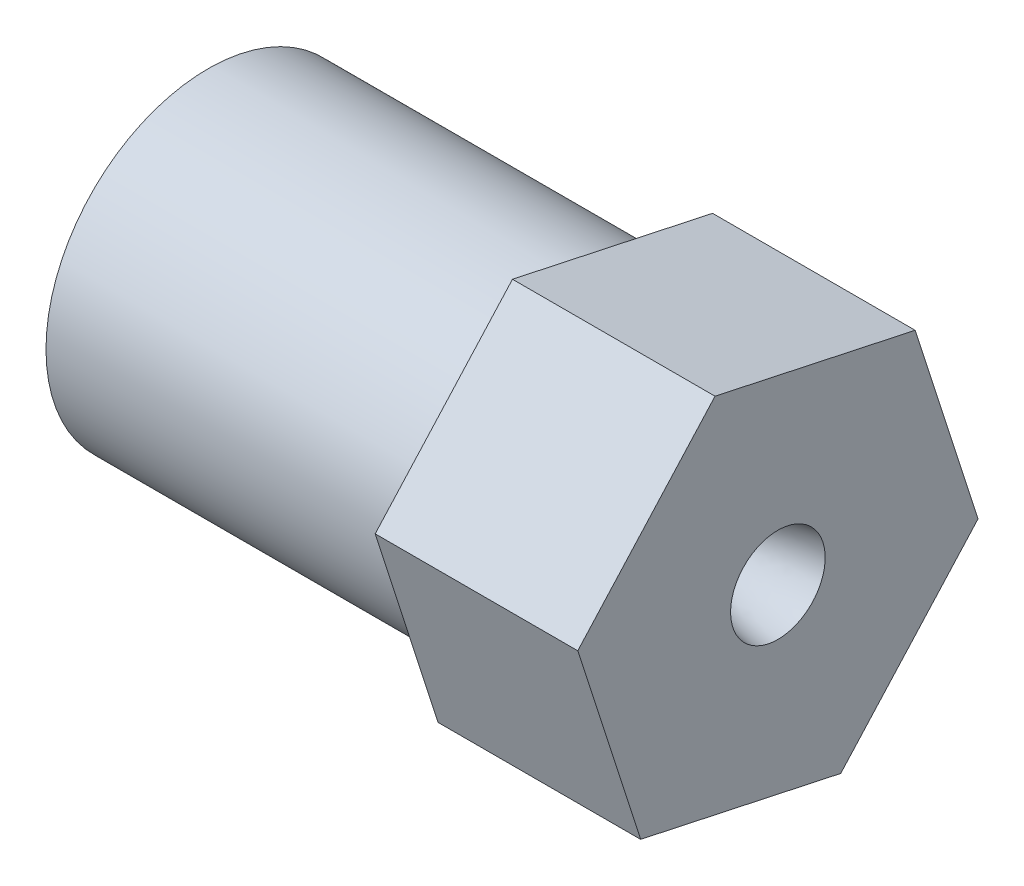
SolidWorks part; units mm, degrees
ref_plane "Front Plane" through (0, 0, 0) normal (0, 0, 1) x (1, 0, 0)
ref_plane "Top Plane" through (0, 0, 0) normal (0, 1, 0) x (1, 0, 0)
ref_plane "Right Plane" through (0, 0, 0) normal (1, 0, 0) x (0, 0, -1)
sketch "Sketch1" plane through (0, 0, 0) normal (0, 0, 1) x (1, 0, 0)
  line L0 (0, 0) -> (3.9748, 0) construction
  line L1 (0.2736, 2.0482) -> (3.9748, 3.3953) construction
  line L2 (-2.1213, 2.8787) -> (-2.7577, 3.5151)
  line L3 (-31.75, 4.445) -> (-31.75, 10.16) construction
  line L4 (-5.0028, 4.445) -> (-31.75, 4.445) construction
  line L5 (-31.75, 10.16) -> (-8.7252, 10.16)
  line L6 (3.9748, 10.16) -> (3.9748, 2.9665)
  line L7 (3.9748, 2.9665) -> (12.9853, 4.2328) construction
  line L8 (-8.7252, 10.16) -> (3.9748, 10.16)
  line L9 (-5.0028, 4.445) -> (-13.462, 4.445)
  line L10 (-19.939, 5.461) -> (-19.939, 6.8199)
  line L11 (-20.066, 6.9469) -> (-24.892, 6.9469)
  line L12 (-24.892, 6.9469) -> (-24.892, 7.8994)
  line L13 (-25.019, 8.0264) -> (-31.115, 8.0264)
  line L14 (-31.75, 10.16) -> (-31.75, 8.6614)
  line L15 (0, 0) -> (-31.75, 0) construction
  line L16 (-13.462, 4.445) -> (-13.462, 4.699)
  line L17 (-13.589, 4.826) -> (-19.304, 4.826)
  arc A0 (-2.1213, 2.8787) -> (0, 2) centre (0, 5) ccw
  arc A1 (0, 2) -> (0.2736, 2.0482) centre (0, 2.8) ccw
  arc A2 (-2.7577, 3.5151) -> (-5.0028, 4.445) centre (-5.0028, 1.27) ccw
  arc A3 (-31.115, 8.0264) -> (-31.75, 8.6614) centre (-31.115, 8.6614) cw
  arc A4 (-19.304, 4.826) -> (-19.939, 5.461) centre (-19.304, 5.461) cw
  arc A5 (-13.462, 4.699) -> (-13.589, 4.826) centre (-13.589, 4.699) ccw
  arc A6 (-19.939, 6.8199) -> (-20.066, 6.9469) centre (-20.066, 6.8199) ccw
  arc A7 (-24.892, 7.8994) -> (-25.019, 8.0264) centre (-25.019, 7.8994) ccw
  parabola Q0 (3.9748, 2.9665) -> (0.2736, 2.0482) focus (3.3244, -6.3338) apex (0.2736, 2.0482)
  point P30 (-31.75, 8.0264)
  point P39 (-24.892, 8.0264)
  dimension "D3" = 3
  dimension "D4" = 0.8
  dimension "D11" = 3.175
  dimension "D12" = 8
  dimension "D14" = 6.9469
  dimension "D20" = 0.635
  dimension "D21" = 0.127
  dimension "D2" = 3.9748
  dimension "D5" = 2.9665
  dimension "D6" = 20
  dimension "D7" = 45
  dimension "D8" = 8.0264
  dimension "D9" = 31.75
  dimension "D10" = 10.16
  dimension "D13" = 12.7
  dimension "D15" = 4.445
  dimension "D16" = 6.858
  dimension "D17" = 11.811
  dimension "D18" = 18.288
  dimension "D19" = 4.826
  dimension "D22" = 2
revolve "Revolve1" add sketch "Sketch1" angle 360 about L0
sketch "Sketch4" plane through (3.9748, 0, 0) normal (1, 0, 0) x (0, 0, -1)
  line L1 (3.9404, -12.2116) -> (12.5458, -2.6933)
  line L2 (12.5458, -2.6933) -> (8.6054, 9.5183)
  line L3 (8.6054, 9.5183) -> (-3.9404, 12.2116)
  line L4 (-3.9404, 12.2116) -> (-12.5458, 2.6933)
  line L5 (-12.5458, 2.6933) -> (-8.6054, -9.5183)
  line L6 (-8.6054, -9.5183) -> (3.9404, -12.2116)
  circle A0 centre (0, 0) radius 10.16
  circle A1 centre (0, 0) radius 10.16 construction
  circle A2 centre (0, 0) radius 11.1125 construction
  circle M1 centre (0, 0) radius 10.16
  dimension "D1" = 22.225
extrude "Boss-Extrude1" add sketch "Sketch4" against normal blind 12.7 contours L4 L5 M1 | L3 L4 M1 | L2 L3 M1 | L1 L2 M1 | L6 L1 M1 | L5 L6 M1
fillet "Fillet1" radius 0.635 1 edges at (-8.7252, 0, -10.16)
equation "\"D3@Sketch1\" = 1.5 * \"D22@Sketch1\""
equation "\"D4@Sketch1\"  = .4 * \"D22@Sketch1\""
equation "\"D5@Sketch1\"=\"D22@Sketch1\" * ( \"er\") ^ .5"
equation "\"er\"= 2.2"
